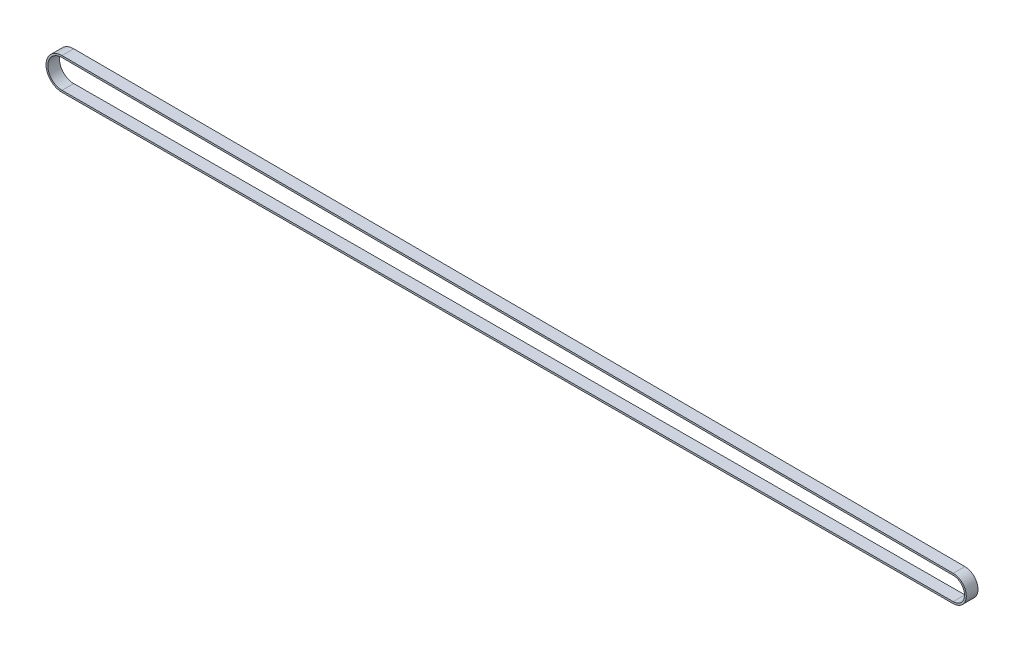
SolidWorks part; units mm, degrees
ref_plane "Front Plane" through (0, 0, 0) normal (0, 0, 1) x (1, 0, 0)
ref_plane "Top Plane" through (0, 0, 0) normal (0, 1, 0) x (1, 0, 0)
ref_plane "Right Plane" through (0, 0, 0) normal (1, 0, 0) x (0, 0, -1)
sketch "Sketch2" plane through (0, 0, 0) normal (0, 0, 1) x (1, 0, 0)
  line L0 (0, 0) -> (1, 0) construction
  line L1 (0, 0) -> (0, 1) construction
  line L2 (0.0165, -43.1247) -> (-380.4797, -44.3247)
  line L3 (-380.4797, -31.4628) -> (0.0165, -32.6628)
  arc A0 (0.0165, -32.6628) -> (0.0165, -43.1247) centre (0, -37.8938) cw
  arc A1 (-380.4797, -44.3247) -> (-380.4797, -31.4628) centre (-380.5, -37.8938) cw
extrude "Extrude-Thin1" add sketch "Sketch2" along normal mid plane 5 thin thin type mid plane wall 0.762
